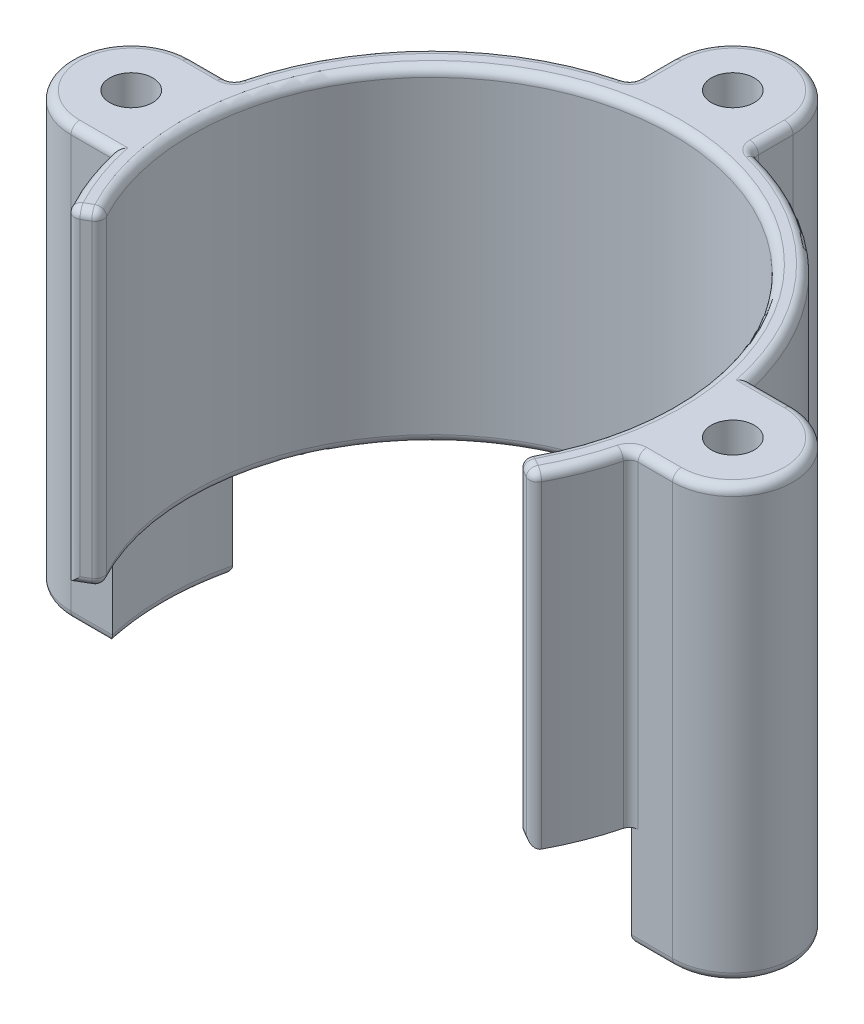
SolidWorks part; units mm, degrees
ref_plane "Front Plane" through (0, 0, 0) normal (0, 0, 1) x (1, 0, 0)
ref_plane "Top Plane" through (0, 0, 0) normal (0, 1, 0) x (1, 0, 0)
ref_plane "Right Plane" through (0, 0, 0) normal (1, 0, 0) x (0, 0, -1)
sketch "Sketch1" plane through (0, 0, 0) normal (0, 1, 0) x (1, 0, 0)
  circle A0 centre (0, 0) radius 15.5
  dimension "D1" = 31
extrude "Body" add sketch "Sketch1" along normal blind 19
sketch "Sketch2" plane through (0, 19, 0) normal (0, 1, 0) x (1, 0, 0)
  line L0 (-17.5, 0) -> (-15.5, 0) construction
  line L1 (-17.5, 3.5) -> (-15.0997, 3.5)
  line L2 (-17.5, -3.5) -> (-15.0997, -3.5)
  arc A0 (-17.5, 3.5) -> (-17.5, -3.5) centre (-17.5, 0) ccw
  circle A3 centre (0, 0) radius 15.5 construction
  arc A4 (-15.0997, -3.5) -> (-15.0997, 3.5) centre (0, 0) cw
  point P2 (0, 0)
  dimension "D2" = 7
  dimension "D1" = 17.5
sketch "Sketch5" plane through (0, 19, 0) normal (0, 1, 0) x (1, 0, 0)
  line L0 (-12.1244, -7) -> (-13.4234, -7.75)
  line L1 (12.1244, -7) -> (13.4234, -7.75)
  line L2 (0, 0) -> (0, -18.3964) construction
  line L3 (12.1244, -7) -> (0, 0) construction
  line L4 (0, 0) -> (-12.0944, -6.9827) construction
  arc A0 (12.1244, -7) -> (-12.1244, -7) centre (0, 0) ccw
  circle A1 centre (0, 0) radius 15.5 construction
  arc A2 (13.4234, -7.75) -> (-13.4234, -7.75) centre (0, 0) cw
  dimension "D1" = 28
  dimension "D2" = 120
extrude "MotorHole" cut sketch "Sketch5" against normal through all contours A0 L0 A2 L1
extrude "Mount" add sketch "Sketch2" against normal blind 25 contours L1 A4 L2 A0
sketch "Sketch8" plane through (0, 19, 0) normal (0, 1, 0) x (1, 0, 0)
  circle A0 centre (-17.5, 0) radius 1.25
  arc A1 (-17.5, 3.5) -> (-17.5, -3.5) centre (-17.5, 0) ccw construction
  dimension "D1" = 2.5
extrude "MountHole" cut sketch "Sketch8" against normal through all
ref_axis "Axis1" through (0, 0, 0) along (0, 1, 0)
pattern_circular "MountS" count 3 over 180 about axis through (0, 0, 0) along (0, 1, 0) of "MountHole", "Mount"
fillet "Fillet4" radius 0.5 35 edges at (12.7739, 19, 7.375) (12.1244, 9.5, 7) (13.4234, 9.5, 7.75) (-12.7739, 0, 7.375) (-13.4234, 9.5, 7.75) (0, 0, -14) (-12.1244, 9.5, 7) (12.7739, 0, 7.375) (0, 19, -14) (-12.7739, 19, 7.375) (-14.419, 19, 5.6871) (-15.5, -6, 0) (-21, -6, 0) (-16.2998, 19, -3.5) (-16.2998, -6, 3.5) (-16.2998, -6, -3.5) (-21, 19, 0) (-16.2998, 19, 3.5) (14.419, 19, 5.6871) (-10.9602, 19, -10.9602) (0, -6, -15.5) (0, -6, -21) (3.5, 19, -16.2998) (-3.5, -6, -16.2998) (3.5, -6, -16.2998) (0, 19, -21) (-3.5, 19, -16.2998) (10.9602, 19, -10.9602) (15.5, -6, 0) (21, -6, 0) (16.2998, 19, 3.5) (16.2998, -6, -3.5) (16.2998, -6, 3.5) (21, 19, 0) (16.2998, 19, -3.5)
equation "\"D1@Sketch1\"=\"MOTOR_D\" + 3"
equation "\"D1@Body\" = \"MOTOR_H\""
equation "\"D1@Sketch5\"=\"MOTOR_D\""
equation "\"D2@Sketch5\" = \"MOTOR_MOUNTANGLE\""
equation "\"MOTOR_D\"= 28"
equation "\"MOTOR_H\"= 19"
equation "\"PITCH_D\"= 44.45"
equation "\"HEX_D\"= 12.7"
equation "\"BODY_THICK\"= 3"
equation "\"TAP_HOLE\" = 2.5"
equation "\"SCREW_HOLE\" = 3"
equation "\"D1@Sketch2\" = \"MOTOR_HOLEDIST\" / 2"
equation "\"D1@Mount\" = \"MOTOR_H\" + 6"
equation "\"MOTOR_HOLEDIST\"= 35"
equation "\"SHAFT_CENTER_OFF\"= 8"
equation "\"SLIPRING_D\" = 12.4"
equation "\"BODY_Y\"= 70"
equation "\"BODY_X\"= 60"
equation "\"BODY_Z\"= 120"
equation "\"BODY_TOPTHICK\"= 4"
equation "\"STAND_R\" = 3"
equation "\"STAND_ZOFF\" = 10"
equation "\"STAND_XOFF\" = 5"
equation "\"MOTOR_ZOFF\" = 25"
equation "\"DRVR_Y\" = 31"
equation "\"DRVR_Z\" = 27"
equation "\"DRVR_YOFF\" = 15"
equation "\"DRVR_ARDOFF\" = 10"
equation "\"BEARING_OD\" = 28.575"
equation "\"BEARING_ID\" = 12.7"
equation "\"BEARING_THICK\" = 7.925"
equation "\"BEARING_FLANGE_D\" = 31.242"
equation "\"BEARING_FLANGETHICK\" = 1.575"
equation "\"COLLAR_OD\" = 20.5"
equation "\"BEARSHAFT_HOLEH\"= 10"
equation "\"CB_W\" = 5"
equation "\"CW_DEPTH\" = 1"
equation "\"PIN_SPACING\" = 2.54"
equation "\"PIN_D\" = 1"
equation "\"MBOARD_ZSPACE\"= 7*\"PIN_SPACING\""
equation "\"MBOARD_XSPACE\"= 7*\"PIN_SPACING\""
equation "\"MBOARD_LXSPACE\"= 1*\"PIN_SPACING\""
equation "\"MBOARD_SCREWX\"= 4"
equation "\"MBOARD_ID\"= 15"
equation "\"MBOARD_OD\"= 4 + \"MBOARD_ID\""
equation "\"PCB_THICK\" = 1.5"
equation "\"SHAFTBASE_ID\"= 12.7"
equation "\"SHAFTBASE_OD\"= \"SHAFTBASE_ID\" + 3"
equation "\"SHAFT_D\" = 18"
equation "\"HEXSHAFT_D\" = 12.75"
equation "\"HEXSHAFT_FILLET\" = 2.5"
equation "\"MOUNTHOLE_DIST\"= 4*\"PIN_SPACING\""
equation "\"MOTOR_MOUNTANGLE\" = 120"
